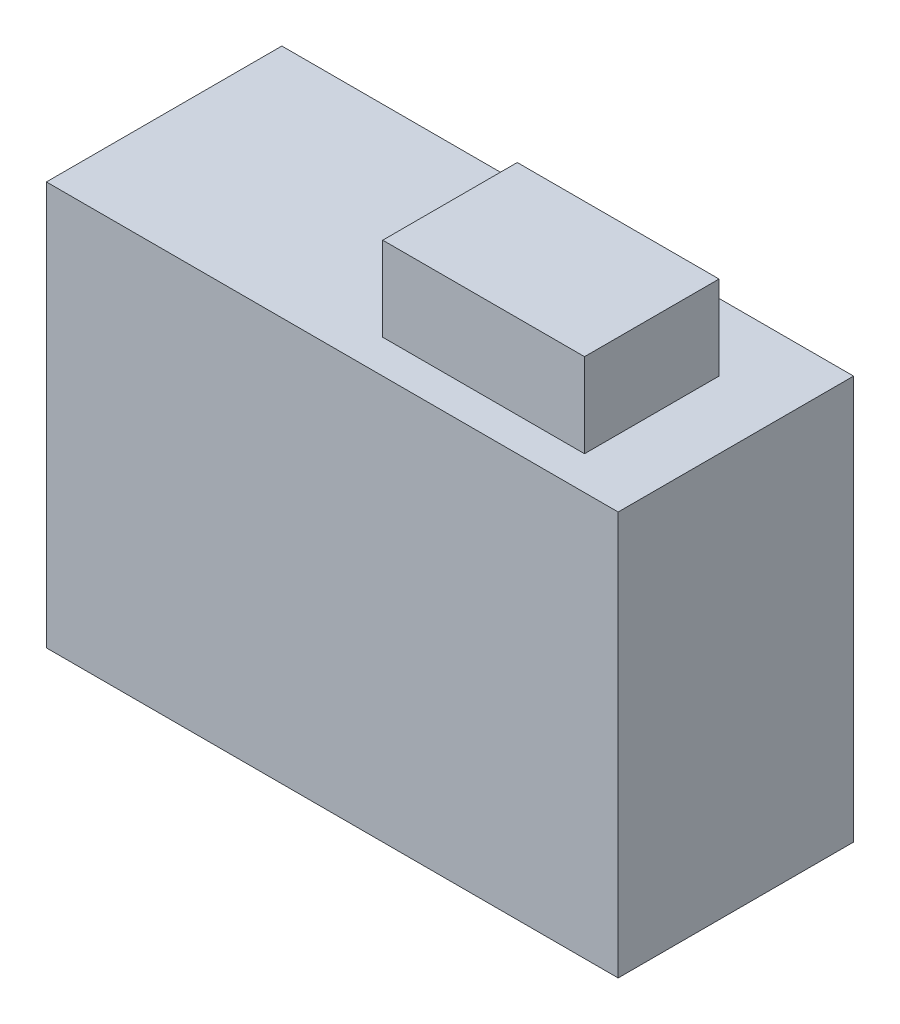
SolidWorks part; units mm, degrees
ref_plane "前视基准面" through (0, 0, 0) normal (0, 0, 1) x (1, 0, 0)
ref_plane "上视基准面" through (0, 0, 0) normal (0, 1, 0) x (1, 0, 0)
ref_plane "右视基准面" through (0, 0, 0) normal (1, 0, 0) x (0, 0, -1)
sketch "草图1" plane through (0, 0, 0) normal (0, 0, 1) x (1, 0, 0)
  line L1 (-49.7022, 31.9514) -> (120.2978, 31.9514)
  line L2 (-49.7022, 31.9514) -> (-49.7022, -88.0486)
  line L3 (-49.7022, -88.0486) -> (120.2978, -88.0486)
  line L4 (120.2978, 31.9514) -> (120.2978, -88.0486)
  dimension "D1" = 170
  dimension "D2" = 120
extrude "凸台-拉伸1" add sketch "草图1" along normal blind 70
sketch "草图2" plane through (0, 31.9514, 0) normal (0, 1, 0) x (1, 0, 0)
  line L0 (120.2978, 0) -> (-49.7022, 0) construction
  line L1 (40.2978, -20) -> (100.2978, -20)
  line L2 (40.2978, -20) -> (40.2978, -60)
  line L3 (40.2978, -60) -> (100.2978, -60)
  line L4 (100.2978, -20) -> (100.2978, -60)
  line L5 (-49.7022, -70) -> (-49.7022, 0) construction
  dimension "D1" = 60
  dimension "D2" = 40
  dimension "D3" = 20
  dimension "D4" = 90
extrude "凸台-拉伸2" add sketch "草图2" along normal blind 25
